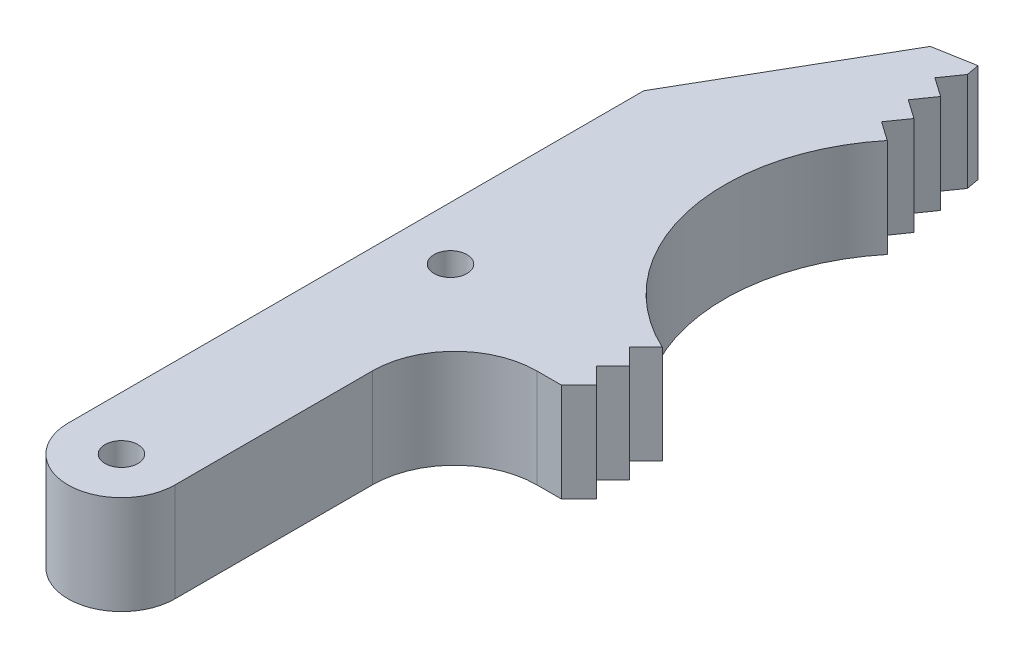
SolidWorks part; units mm, degrees
ref_plane "Alzado" through (0, 0, 0) normal (0, 0, 1) x (1, 0, 0)
ref_plane "Planta" through (0, 0, 0) normal (0, 1, 0) x (1, 0, 0)
ref_plane "Vista lateral" through (0, 0, 0) normal (1, 0, 0) x (0, 0, -1)
sketch "Croquis2" plane through (0, 0, 0) normal (0, 1, 0) x (1, 0, 0)
  line L0 (11.4519, 91.3762) -> (12.1465, 87.437) construction
  line L1 (9.8296, 89.0593) -> (11.7992, 89.4066) construction
  line L2 (12.1465, 87.437) -> (12.8411, 83.4977) construction
  line L3 (10.5241, 85.1201) -> (12.4938, 85.4673) construction
  line L4 (12.8411, 83.4977) -> (13.5357, 79.5585) construction
  line L5 (13.1884, 81.5281) -> (11.2187, 81.1808) construction
  line L6 (21.6213, 44.1213) -> (21.6213, 40.1213) construction
  line L7 (21.6213, 42.1213) -> (19.6213, 42.1213) construction
  line L8 (21.6213, 40.1213) -> (21.6213, 36.1213) construction
  line L9 (21.6213, 38.1213) -> (19.6213, 38.1213) construction
  line L36 (-6.5, 70) -> (-6.5, 0)
  line L37 (6.5, 0) -> (6.5, 24)
  line L38 (16.5, 34) -> (19.5, 34)
  line L39 (19.5, 34) -> (21.6213, 36.1213)
  line L40 (21.6213, 36.1213) -> (19.6213, 38.1213)
  line L41 (19.6213, 38.1213) -> (21.6213, 40.1213)
  line L42 (21.6213, 40.1213) -> (19.6213, 42.1213)
  line L43 (19.6213, 42.1213) -> (21.6213, 44.1213)
  line L45 (13.5357, 79.5585) -> (11.2187, 81.1808)
  line L46 (11.2187, 81.1808) -> (12.8411, 83.4977)
  line L47 (12.8411, 83.4977) -> (10.5241, 85.1201)
  line L48 (10.5241, 85.1201) -> (12.1465, 87.437)
  line L49 (12.1465, 87.437) -> (9.8296, 89.0593)
  line L50 (9.8296, 89.0593) -> (11.4519, 91.3762)
  line L51 (11.4519, 91.3762) -> (11.174, 92.9519)
  line L52 (11.174, 92.9519) -> (6.25, 92.0836)
  line L53 (6.25, 92.0836) -> (-6.5, 70)
  circle A0 centre (0, 0) radius 2
  arc A11 (-6.5, 0) -> (6.5, 0) centre (0, 0) ccw
  arc A12 (16.5, 34) -> (6.5, 24) centre (16.5, 24) ccw
  arc A13 (13.5357, 79.5585) -> (21.6213, 44.1213) centre (31.3216, 64.9757) ccw
  dimension "D1" = 6.5
  dimension "D2" = 10
  dimension "D5" = 25.5
  dimension "D11" = 23
  dimension "D13" = 4
  dimension "D3" = 24
  dimension "D4" = 70
  dimension "D6" = 150
  dimension "D7" = 130
  dimension "D8" = 5
  dimension "D9" = 90
  dimension "D10" = 1.6
  dimension "D12" = 4
  dimension "D14" = 3
  dimension "D15" = 3
extrude "Saliente-Extruir1" add sketch "Croquis2" along normal blind 12
sketch "Sketch1" plane through (0, 12, 0) normal (0, 1, 0) x (1, 0, 0)
  line L0 (0, 0) -> (0, 40) construction
  circle A0 centre (0, 40) radius 2
  dimension "D2" = 4
  dimension "D1" = 40
extrude "Cut-Extrude1" cut sketch "Sketch1" against normal through all
